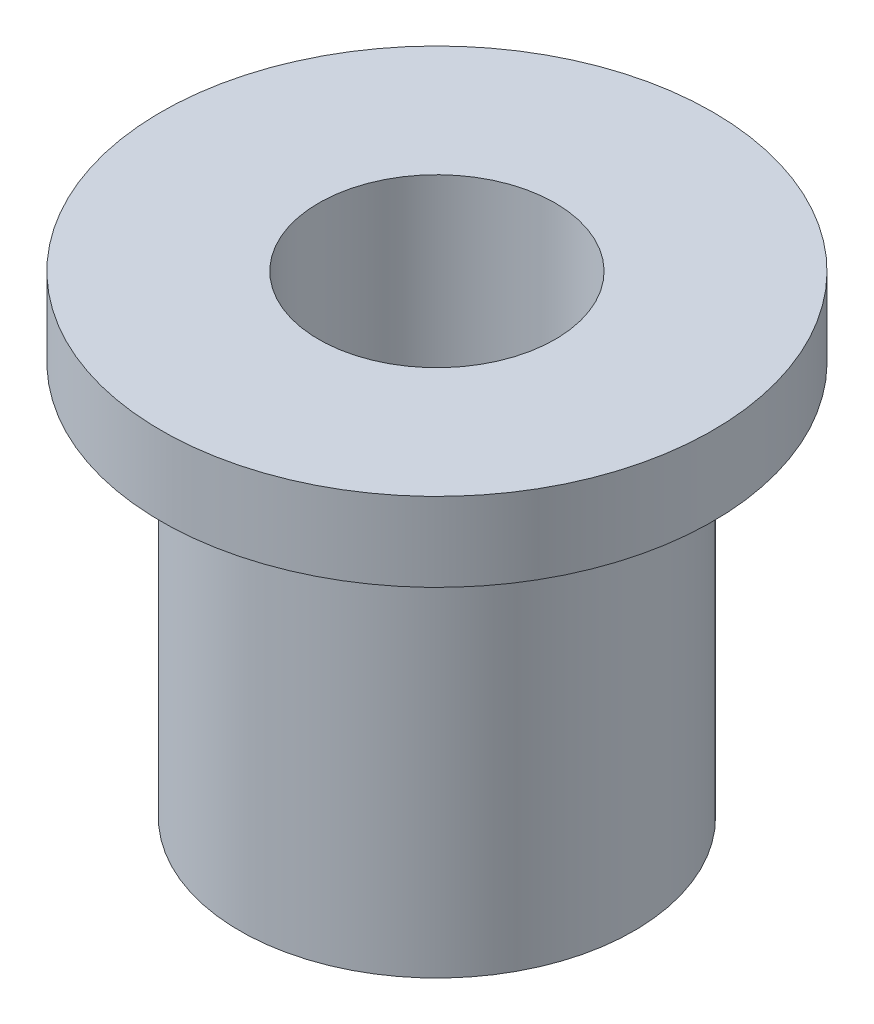
SolidWorks part; units mm, degrees
ref_plane "Front Plane" through (0, 0, 0) normal (0, 0, 1) x (1, 0, 0)
ref_plane "Top Plane" through (0, 0, 0) normal (0, 1, 0) x (1, 0, 0)
ref_plane "Right Plane" through (0, 0, 0) normal (1, 0, 0) x (0, 0, -1)
sketch "Sketch1" plane through (0, 0, 0) normal (0, 0, 1) x (1, 0, 0)
  line L0 (0, 0) -> (0, 4.2685) construction
  line L1 (4.5, 0) -> (7.5, 0)
  line L2 (7.5, 0) -> (7.5, 15)
  line L3 (7.5, 15) -> (10.5, 15)
  line L4 (10.5, 15) -> (10.5, 18)
  line L5 (10.5, 18) -> (4.5, 18)
  line L6 (4.5, 18) -> (4.5, 0)
  dimension "D1" = 3
  dimension "D2" = 4.5
  dimension "D3" = 3
  dimension "D4" = 3
  dimension "D5" = 15
revolve "Revolve1" add sketch "Sketch1" angle 360 about L0
